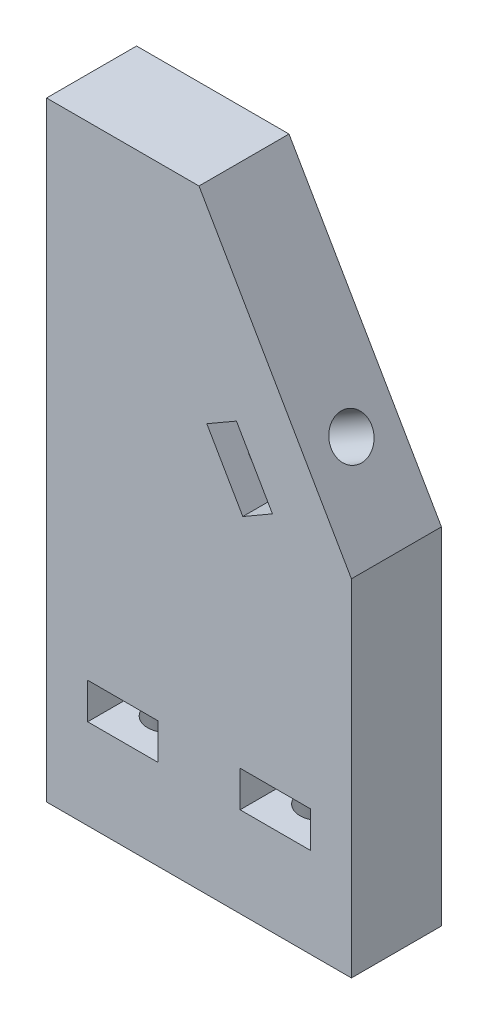
SolidWorks part; units mm, degrees
ref_plane "Front Plane" through (0, 0, 0) normal (0, 0, 1) x (1, 0, 0)
ref_plane "Top Plane" through (0, 0, 0) normal (0, 1, 0) x (1, 0, 0)
ref_plane "Right Plane" through (0, 0, 0) normal (1, 0, 0) x (0, 0, -1)
sketch "Sketch1" plane through (0, 0, 0) normal (0, 0, 1) x (1, 0, 0)
  line L0 (0, -28.803) -> (0, 28.803)
  line L1 (0, 28.803) -> (-25.4, 72.797)
  line L2 (-25.4, 72.797) -> (-25.4, -28.803) construction
  line L3 (-25.4, -28.803) -> (0, -28.803)
  line L4 (-25.4, 72.797) -> (-50.8, 72.797)
  line L5 (-50.8, 72.797) -> (-50.8, -28.803)
  line L6 (-50.8, -28.803) -> (-25.4, -28.803)
  point P4 (0, 0)
  dimension "D1" = 30
  dimension "D2" = 50.8
  dimension "D3" = 101.6
  dimension "D4" = 50.8
extrude "Boss-Extrude1" add sketch "Sketch1" along normal mid plane 15
sketch "Sketch2" plane through (12.472, 7.2007, 0) normal (0.866, 0.5, 0) x (0, 0, -1)
  line L0 (0, 24.9441) -> (0, 75.7441) construction
  line L1 (-7.5, 24.9441) -> (7.5, 24.9441) construction
  line L2 (3.4641, 33.9441) -> (7.5, 33.9441)
  line L3 (-7.5, 75.7441) -> (7.5, 75.7441) construction
  line L4 (6.9282, 39.9441) -> (3.4641, 45.9441) construction
  line L5 (3.4641, 45.9441) -> (-3.4641, 45.9441)
  line L6 (-3.4641, 45.9441) -> (-6.9282, 39.9441) construction
  line L7 (-6.9282, 39.9441) -> (-3.4641, 33.9441) construction
  line L8 (-3.4641, 33.9441) -> (3.4641, 33.9441)
  line L9 (3.4641, 33.9441) -> (6.9282, 39.9441) construction
  line L10 (7.5, 24.9441) -> (7.5, 75.7441) construction
  line L13 (7.5, 33.9441) -> (7.5, 45.9441)
  line L14 (7.5, 45.9441) -> (3.4641, 45.9441)
  line L15 (-3.4641, 45.9441) -> (-7.5, 45.9441)
  line L16 (-7.5, 24.9441) -> (-7.5, 75.7441) construction
  line L17 (-7.5, 45.9441) -> (-7.5, 33.9441)
  line L18 (-7.5, 33.9441) -> (-3.4641, 33.9441)
  line L19 (0, 39.9441) -> (6.9282, 39.9441) construction
  circle A0 centre (0, 39.9441) radius 6 construction
  dimension "D1" = 12
  dimension "D2" = 15
extrude "Cut-Extrude1" cut sketch "Sketch2" against normal blind 5.7 from offset 10 offset against normal yes
hole_wizard "17/64 (0.26563) Diameter Hole1" positions "Sketch4" profile "Sketch5" hole size "17/64" standard "ANSI Inch"
sketch "Sketch4" plane through (3.8118, 2.2007, 0) normal (-0.866, -0.5, 0) x (0, 0, 1)
  line L3 (7.5, 33.9441) -> (-7.5, 45.9441) construction
  point P0 (0, 39.9441)
  point P26 (0, 39.9441)
sketch "Sketch5" plane through (-16.1603, 36.7933, 0) normal (0, 0, 1) x (0.5, -0.866, 0)
  line L0 (0, 0) -> (0, 31.997)
  line L1 (0, 31.997) -> (3.3735, 31.997)
  line L2 (3.3735, 31.997) -> (3.3735, 0)
  line L5 (3.3735, 0) -> (0, 0)
  line L11 (0, -6.35) -> (0, 107.95) construction
  dimension "Thru Hole Dia." = 6.747
  dimension "Thru Hole Depth" = 31.997
sketch "Sketch6" plane through (0, -28.803, 0) normal (0, -1, 0) x (1, 0, 0)
  line L0 (-50.8, 0) -> (0, 0) construction
  line L1 (-50.8, 7.5) -> (-50.8, -7.5) construction
  line L2 (0, 7.5) -> (0, -7.5) construction
  line L3 (-38.1, 0) -> (-38.1, 6.755) construction
  line L4 (-38.1, 6.755) -> (-43.95, 3.3775) construction
  line L5 (-43.95, 3.3775) -> (-43.95, -3.3775)
  line L6 (-43.95, -3.3775) -> (-38.1, -6.755) construction
  line L7 (-38.1, -6.755) -> (-32.25, -3.3775) construction
  line L8 (-32.25, -3.3775) -> (-32.25, 3.3775)
  line L9 (-32.25, 3.3775) -> (-38.1, 6.755) construction
  line L10 (-18.55, 3.3775) -> (-18.55, -3.3775)
  line L11 (-18.55, -3.3775) -> (-12.7, -6.755) construction
  line L12 (-12.7, -6.755) -> (-6.85, -3.3775) construction
  line L13 (-6.85, -3.3775) -> (-6.85, 3.3775)
  line L14 (-6.85, 3.3775) -> (-12.7, 6.755) construction
  line L15 (-12.7, 6.755) -> (-18.55, 3.3775) construction
  line L16 (-12.7, 0) -> (-12.7, 6.755) construction
  line L17 (-18.55, -3.3775) -> (-18.55, -7.5)
  line L18 (-50.8, -7.5) -> (0, -7.5) construction
  line L19 (-18.55, -7.5) -> (-6.85, -7.5)
  line L20 (-6.85, -7.5) -> (-6.85, -3.3775)
  line L21 (-6.85, 3.3775) -> (-6.85, 7.5)
  line L22 (-50.8, 7.5) -> (0, 7.5) construction
  line L23 (-6.85, 7.5) -> (-18.55, 7.5)
  line L24 (-18.55, 7.5) -> (-18.55, 3.3775)
  line L25 (-32.25, -3.3775) -> (-32.25, -7.5)
  line L26 (-32.25, -7.5) -> (-43.95, -7.5)
  line L27 (-43.95, -7.5) -> (-43.95, -3.3775)
  line L28 (-43.95, 3.3775) -> (-43.95, 7.5)
  line L29 (-43.95, 7.5) -> (-32.25, 7.5)
  line L30 (-32.25, 7.5) -> (-32.25, 3.3775)
  circle A0 centre (-38.1, 0) radius 5.85 construction
  circle A1 centre (-12.7, 0) radius 5.85 construction
  dimension "D1" = 11.7
  dimension "D2" = 12.7
  dimension "D3" = 12.7
extrude "Cut-Extrude2" cut sketch "Sketch6" against normal blind 6 from offset 15 offset against normal yes
hole_wizard "17/64 (0.26563) Diameter Hole2" positions "Sketch7" profile "Sketch8" hole size "17/64" standard "ANSI Inch"
sketch "Sketch7" plane through (0, -13.803, 0) normal (0, 1, 0) x (1, 0, 0)
  line L2 (-32.25, -7.5) -> (-43.95, 7.5) construction
  line L4 (-18.55, 7.5) -> (-6.85, -7.5) construction
  point P7 (-38.1, 0)
  point P16 (-12.7, 0)
  point P30 (-12.7, 0)
sketch "Sketch8" plane through (-38.1, -13.803, 0) normal (1, 0, 0) x (0, 0, 1)
  line L0 (0, 0) -> (0, 15)
  line L1 (0, 15) -> (3.3735, 15)
  line L2 (3.3735, 15) -> (3.3735, 0)
  line L5 (3.3735, 0) -> (0, 0)
  line L11 (0, -6.35) -> (0, 107.95) construction
  dimension "Thru Hole Dia." = 6.747
  dimension "Thru Hole Depth" = 15
sketch "Sketch10" plane through (0, -28.803, 0) normal (0, -1, 0) x (1, 0, 0)
  circle A0 centre (-38.1, 0) radius 3.3735
  circle A1 centre (-12.7, 0) radius 3.3735
  circle A2 centre (-12.7, 0) radius 3.3735 construction
  circle A3 centre (-38.1, 0) radius 3.3735 construction
extrude "Cut-Extrude4" cut sketch "Sketch10" against normal offset from surface (31 mm away) 10 up to face at (-38.1, -7.803, 0) offset beyond the face yes
sketch "Sketch11" plane through (12.472, 7.2007, 0) normal (0.866, 0.5, 0) x (0, 0, -1)
  circle A0 centre (0, 39.9441) radius 3.3735
  circle A1 centre (0, 39.9441) radius 3.3735 construction
extrude "Cut-Extrude5" cut sketch "Sketch11" against normal offset from surface (25.7 mm away) 10 up to face at (-21.0966, 33.9433, 0) offset beyond the face yes
